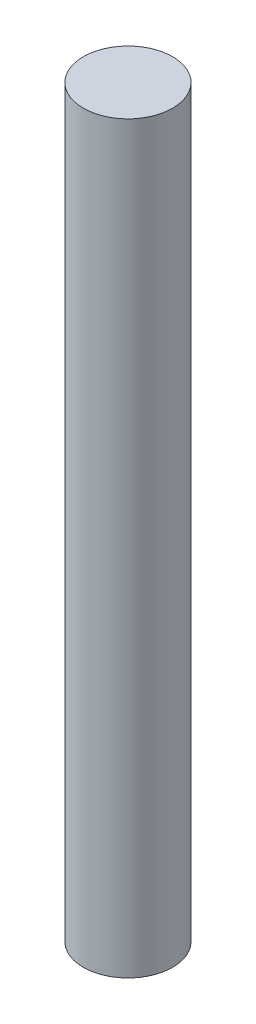
SolidWorks part; units mm, degrees
ref_plane "前视基准面" through (0, 0, 0) normal (0, 0, 1) x (1, 0, 0)
ref_plane "上视基准面" through (0, 0, 0) normal (0, 1, 0) x (1, 0, 0)
ref_plane "右视基准面" through (0, 0, 0) normal (1, 0, 0) x (0, 0, -1)
other "Configuration Table"
sketch "草图1" plane through (0, 0, 0) normal (0, 1, 0) x (1, 0, 0)
  circle A0 centre (-3.1399, -1.6234) radius 0.6
  dimension "D1" = 1.2
extrude "凸台-拉伸1" add sketch "草图1" along normal blind 10
